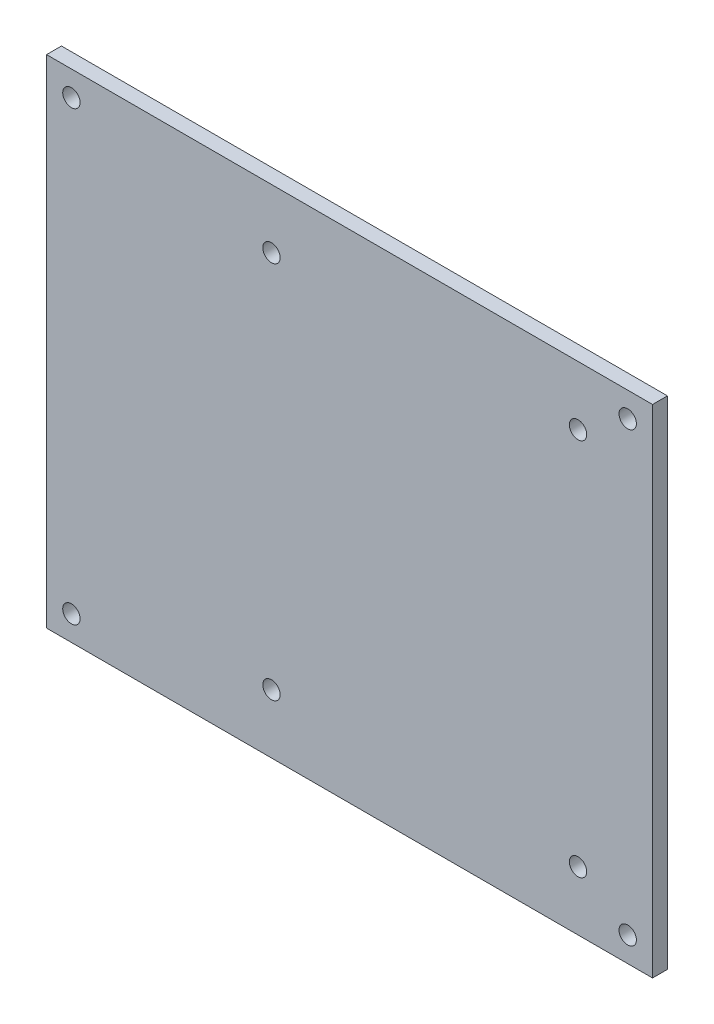
SolidWorks part; units mm, degrees
ref_plane "Front Plane" through (0, 0, 0) normal (1, 0, 0) x (0, 1, 0)
ref_plane "Top Plane" through (0, 0, 0) normal (0, 0, 1) x (0, 1, 0)
ref_plane "Right Plane" through (0, 0, 0) normal (0, 1, 0) x (-1, 0, 0)
sketch "Sketch1" plane through (0, 0, 0) normal (0, 0, 1) x (0, 1, 0)
  line L1 (50, -61) -> (-50, -61)
  line L2 (50, -61) -> (50, 61)
  line L3 (50, 61) -> (-50, 61)
  line L4 (-50, -61) -> (-50, 61)
  line L5 (50, -61) -> (-50, 61) construction
  line L6 (50, 61) -> (-50, -61) construction
  circle A0 centre (-45, 56) radius 1.75
  circle A1 centre (45, 56) radius 1.75
  circle A2 centre (-45, -56) radius 1.75
  circle A3 centre (45, -56) radius 1.75
  circle A4 centre (-38.1, -46) radius 1.75
  circle A5 centre (38.1, -46) radius 1.75
  circle A6 centre (-38.1, 15.72) radius 1.75
  circle A7 centre (38.1, 15.72) radius 1.75
  point P0 (0, 0)
  point P20 (0, 0)
  point P21 (0, 0)
  point P22 (0, 0)
  point P25 (0, 0)
  dimension "D2" = 3.5
  dimension "D8" = 3.5
  dimension "D1" = 122
  dimension "D3" = 90
  dimension "D4" = 112
  dimension "D5" = 56
  dimension "D6" = 100
  dimension "D7" = 5
  dimension "D9" = 61.72
  dimension "D10" = 76.2
  dimension "D11" = 38.1
  dimension "D12" = 15
extrude "Boss-Extrude1" add sketch "Sketch1" along normal blind 3
equation "\"D11@Sketch1\"=76.2/2"
